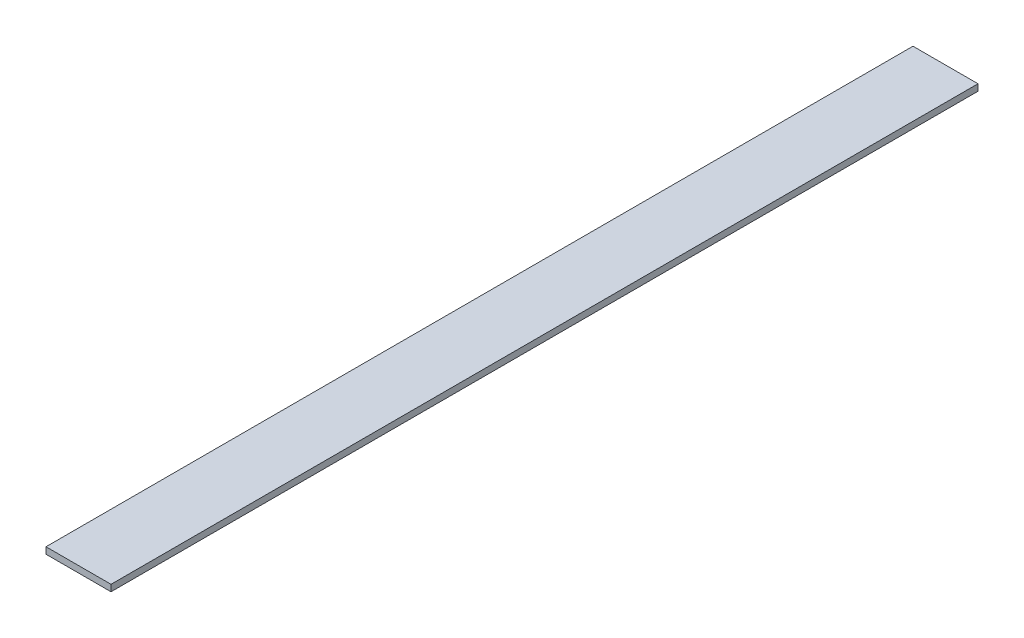
SolidWorks part; units mm, degrees
material "Balsa"
ref_plane "Front Plane" through (0, 0, 0) normal (0, 0, 1) x (1, 0, 0)
ref_plane "Top Plane" through (0, 0, 0) normal (0, 1, 0) x (1, 0, 0)
ref_plane "Right Plane" through (0, 0, 0) normal (1, 0, 0) x (0, 0, -1)
sketch "Sketch1" plane through (0, 0, 0) normal (0, 1, 0) x (1, 0, 0)
  line L1 (-36.5161, 312.7563) -> (-6.5161, 312.7563)
  line L2 (-36.5161, 312.7563) -> (-36.5161, -87.2437)
  line L3 (-36.5161, -87.2437) -> (-6.5161, -87.2437)
  line L4 (-6.5161, 312.7563) -> (-6.5161, -87.2437)
  line L5 (-36.5161, 312.7563) -> (-6.5161, -87.2437) construction
  line L6 (-36.5161, -87.2437) -> (-6.5161, 312.7563) construction
  point P0 (-21.5161, 112.7563)
  dimension "D1" = 400
  dimension "D2" = 30
extrude "Boss-Extrude1" add sketch "Sketch1" along normal blind 3
